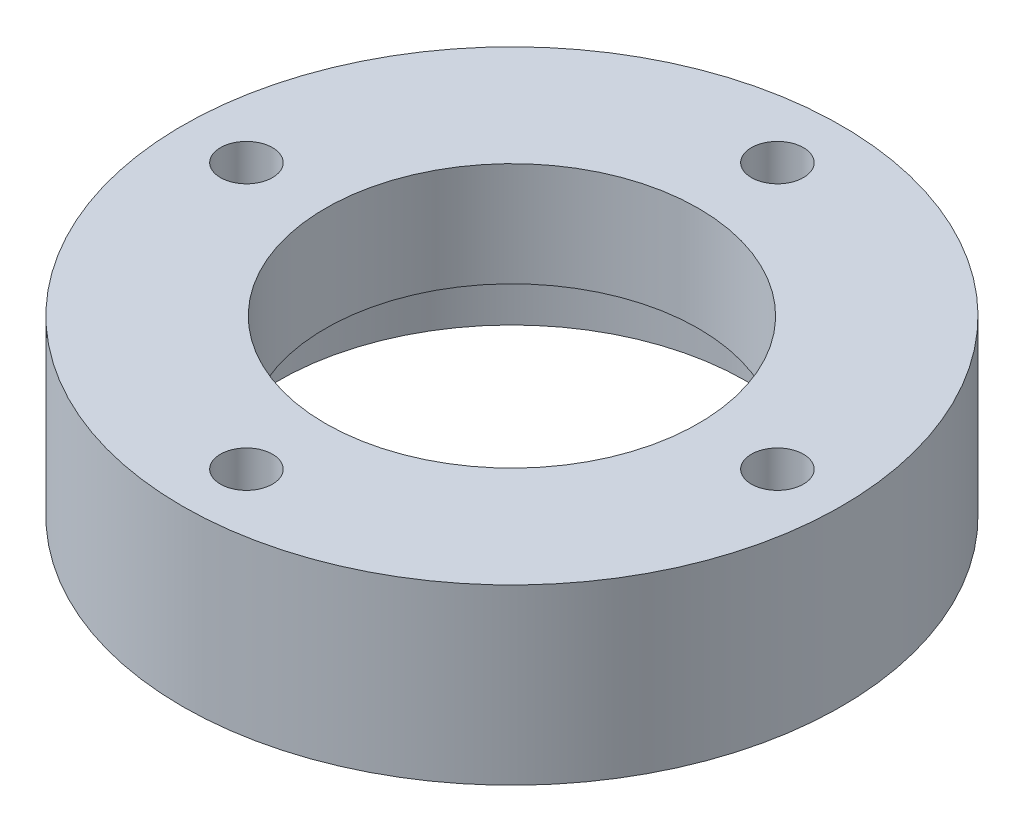
SolidWorks part; units mm, degrees
ref_plane "Front Plane" through (0, 0, 0) normal (0, 0, 1) x (1, 0, 0)
ref_plane "Top Plane" through (0, 0, 0) normal (0, 1, 0) x (1, 0, 0)
ref_plane "Right Plane" through (0, 0, 0) normal (1, 0, 0) x (0, 0, -1)
sketch "Sketch1" plane through (0, 0, 0) normal (0, 1, 0) x (1, 0, 0)
  circle A0 centre (0, 0) radius 10.75
  circle A1 centre (0, 0) radius 19
extrude "Extrude1" add sketch "Sketch1" along normal blind 10
sketch "Sketch2" plane through (0, 0, 0) normal (0, -1, 0) x (1, 0, 0)
  circle A0 centre (0, 0) radius 13.5
extrude "Cut-Extrude1" cut sketch "Sketch2" against normal blind 4
sketch "Sketch3" plane through (0, 10, 0) normal (0, 1, 0) x (1, 0, 0)
  circle A0 centre (0, 15.305) radius 1.5
  circle A2 centre (15.305, 0) radius 1.5
  circle A3 centre (0, -15.305) radius 1.5
  circle A4 centre (-15.305, 0) radius 1.5
extrude "Cut-Extrude2" cut sketch "Sketch3" against normal through all
